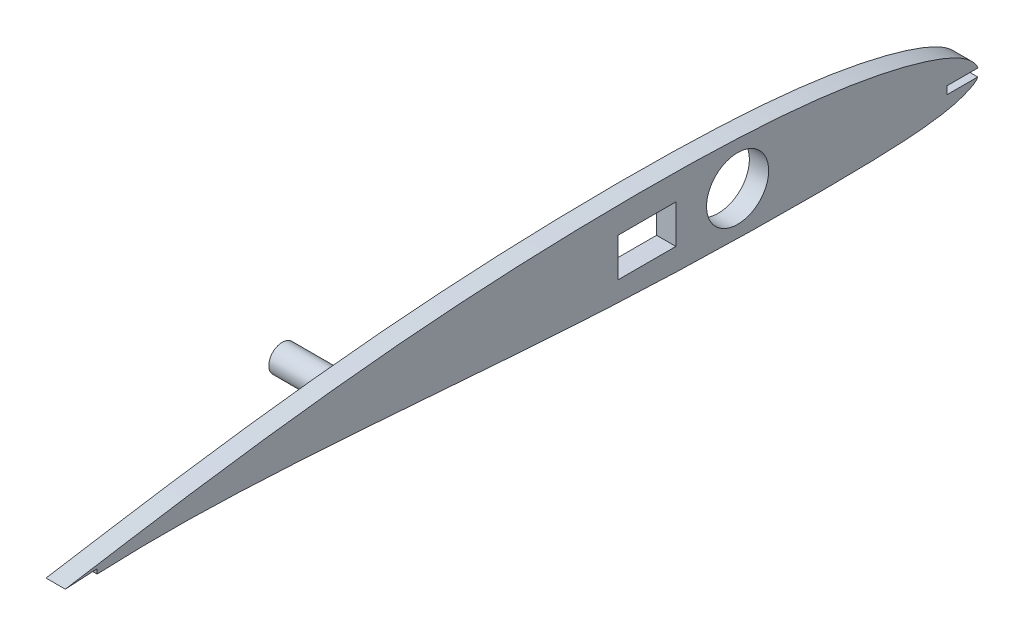
SolidWorks part; units mm, degrees
material "Manual Density from Real Component Centina"
ref_plane "Piano frontale" through (0, 0, 0) normal (0, 0, 1) x (1, 0, 0)
ref_plane "Piano superiore" through (0, 0, 0) normal (0, 1, 0) x (1, 0, 0)
ref_plane "Piano destro" through (0, 0, 0) normal (1, 0, 0) x (0, 0, -1)
curve "Curva1"
  spline degree 3 poles (0, 0.1724, 248.285) (0, -0.053, 250.4273) (0, 0.2462, 248.3284) (0, 0.5529, 246.6445) (0, 1.2459, 242.6221) (0, 2.0989, 237.7464) (0, 3.1818, 231.3634) (0, 4.2933, 223.9772) (0, 5.7312, 215.5604) (0, 7.1315, 206.3004) (0, 8.6324, 196.1631) (0, 10.1162, 185.3524) (0, 11.5493, 173.9891) (0, 12.8816, 162.1914) (0, 14.0593, 150.0724) (0, 15.0523, 137.7438) (0, 15.8256, 125.3116) (0, 16.3834, 112.8888) (0, 16.7267, 100.597) (0, 16.8648, 88.5669) (0, 16.792, 76.9314) (0, 16.4941, 65.8165) (0, 15.9609, 55.3329) (0, 15.1594, 45.573) (0, 14.0978, 36.6074) (0, 12.7884, 28.4972) (0, 11.2839, 21.2988) (0, 9.6413, 15.0749) (0, 7.9136, 9.8809) (0, 6.1182, 5.7699) (0, 4.2384, 2.7289) (0, 2.3057, 0.8126) (0, 0.7927, 0.0312) (0, -0.4105, -0.0213) (0, -1.7115, 0.4949) (0, -2.8658, 2.6253) (0, -4.0404, 5.6977) (0, -4.9287, 10.0719) (0, -5.5974, 15.6262) (0, -6.0122, 22.4122) (0, -6.265, 30.3619) (0, -6.3814, 39.3972) (0, -6.3554, 49.3987) (0, -6.2185, 60.2453) (0, -5.9476, 71.8018) (0, -5.5368, 83.9408) (0, -4.9386, 96.5461) (0, -4.1527, 109.5201) (0, -3.2196, 122.7671) (0, -2.1909, 136.1764) (0, -1.148, 149.6158) (0, -0.1602, 162.9314) (0, 0.706, 175.9537) (0, 1.3896, 188.4999) (0, 1.8332, 200.3712) (0, 1.9676, 211.3376) (0, 1.8232, 221.1842) (0, 1.4973, 229.6804) (0, 1.0741, 236.8065) (0, 0.6857, 242.1894) (0, 0.3087, 246.5181) (0, 0.1724, 248.285) (0, -0.053, 250.4273) (0, 0.2462, 248.3284) knots -0.014202 -0.006329 -0.001589 0 0.001576 0.006211 0.01368 0.023764 0.036307 0.051658 0.068045 0.086769 0.107053 0.128647 0.151303 0.174786 0.19886 0.223309 0.247929 0.272522 0.296848 0.320648 0.343669 0.365658 0.3864 0.405741 0.423561 0.439779 0.454311 0.467034 0.477831 0.486643 0.493542 0.498786 0.50271 0.50309 0.505896 0.510322 0.516831 0.525521 0.536535 0.549945 0.565696 0.583577 0.603379 0.624844 0.647727 0.671743 0.696673 0.722357 0.748609 0.77521 0.801891 0.828329 0.854175 0.879074 0.902636 0.924421 0.943939 0.960827 0.974827 0.985798 0.993671 0.998411 1 1.001576 1.006211 1.01368 periodic
sketch "Schizzo1" plane through (0, 0, 0) normal (1, 0, 0) x (0, 0, -1)
  line L0 (-250, 0) -> (0.0001, 0.0174) construction
  line L1 (0.0001, 0.0174) -> (-0.0034, 50.0174) construction
  line L2 (-62.4999, 16.3096) -> (-62.4999, -6.155) construction
  line L4 (-78.4999, 10.0773) -> (-93.4999, 10.0773)
  line L5 (-78.4999, 10.0773) -> (-78.4999, 0.0773)
  line L6 (-78.4999, 0.0773) -> (-93.4999, 0.0773)
  line L7 (-93.4999, 10.0773) -> (-93.4999, 0.0773)
  circle A0 centre (-62.4999, 5.0773) radius 8.05
  spline S0 degree 3 poles (-248.3284, 0.2462) (-250.4273, -0.053) (-248.285, 0.1724) (-246.5181, 0.3087) (-242.1894, 0.6857) (-236.8065, 1.0741) (-229.6804, 1.4973) (-221.1842, 1.8232) (-211.3376, 1.9676) (-200.3712, 1.8332) (-188.4999, 1.3896) (-175.9537, 0.706) (-162.9314, -0.1602) (-149.6158, -1.148) (-136.1764, -2.1909) (-122.7671, -3.2196) (-109.5201, -4.1527) (-96.5461, -4.9386) (-83.9408, -5.5368) (-71.8018, -5.9476) (-60.2453, -6.2185) (-49.3987, -6.3554) (-39.3972, -6.3814) (-30.3619, -6.265) (-22.4122, -6.0122) (-15.6262, -5.5974) (-10.0719, -4.9287) (-5.6977, -4.0404) (-2.6253, -2.8658) (-0.4949, -1.7115) (0.0213, -0.4105) (-0.0312, 0.7927) (-0.8126, 2.3057) (-2.7289, 4.2384) (-5.7699, 6.1182) (-9.8809, 7.9136) (-15.0749, 9.6413) (-21.2988, 11.2839) (-28.4972, 12.7884) (-36.6074, 14.0978) (-45.573, 15.1594) (-55.3329, 15.9609) (-65.8165, 16.4941) (-76.9314, 16.792) (-88.5669, 16.8648) (-100.597, 16.7267) (-112.8888, 16.3834) (-125.3116, 15.8256) (-137.7438, 15.0523) (-150.0724, 14.0593) (-162.1914, 12.8816) (-173.9891, 11.5493) (-185.3524, 10.1162) (-196.1631, 8.6324) (-206.3004, 7.1315) (-215.5604, 5.7312) (-223.9772, 4.2933) (-231.3634, 3.1818) (-237.7464, 2.0989) (-242.6221, 1.2459) (-246.6445, 0.5529) (-248.3284, 0.2462) (-250.4273, -0.053) (-248.285, 0.1724) knots -0.01368 -0.006211 -0.001576 0 0.001589 0.006329 0.014202 0.025173 0.039173 0.056061 0.075579 0.097364 0.120926 0.145825 0.171671 0.198109 0.22479 0.251391 0.277643 0.303327 0.328257 0.352273 0.375156 0.396621 0.416423 0.434304 0.450055 0.463465 0.474479 0.483169 0.489678 0.494104 0.49691 0.49729 0.501214 0.506458 0.513357 0.522169 0.532966 0.545689 0.560221 0.576439 0.594259 0.6136 0.634342 0.656331 0.679352 0.703152 0.727478 0.752071 0.776691 0.80114 0.825214 0.848697 0.871353 0.892947 0.913231 0.931955 0.948342 0.963693 0.976236 0.98632 0.993789 0.998424 1 1.001589 1.006329 1.014202 only from (-250, 0) to (-250, 0) construction
  spline S1 degree 3 poles (-248.3284, 0.2462) (-250.4273, -0.053) (-248.285, 0.1724) (-246.5181, 0.3087) (-242.1894, 0.6857) (-236.8065, 1.0741) (-229.6804, 1.4973) (-221.1842, 1.8232) (-211.3376, 1.9676) (-200.3712, 1.8332) (-188.4999, 1.3896) (-175.9537, 0.706) (-162.9314, -0.1602) (-149.6158, -1.148) (-136.1764, -2.1909) (-122.7671, -3.2196) (-109.5201, -4.1527) (-96.5461, -4.9386) (-83.9408, -5.5368) (-71.8018, -5.9476) (-60.2453, -6.2185) (-49.3987, -6.3554) (-39.3972, -6.3814) (-30.3619, -6.265) (-22.4122, -6.0122) (-15.6262, -5.5974) (-10.0719, -4.9287) (-5.6977, -4.0404) (-2.6253, -2.8658) (-0.4949, -1.7115) (0.0213, -0.4105) (-0.0312, 0.7927) (-0.8126, 2.3057) (-2.7289, 4.2384) (-5.7699, 6.1182) (-9.8809, 7.9136) (-15.0749, 9.6413) (-21.2988, 11.2839) (-28.4972, 12.7884) (-36.6074, 14.0978) (-45.573, 15.1594) (-55.3329, 15.9609) (-65.8165, 16.4941) (-76.9314, 16.792) (-88.5669, 16.8648) (-100.597, 16.7267) (-112.8888, 16.3834) (-125.3116, 15.8256) (-137.7438, 15.0523) (-150.0724, 14.0593) (-162.1914, 12.8816) (-173.9891, 11.5493) (-185.3524, 10.1162) (-196.1631, 8.6324) (-206.3004, 7.1315) (-215.5604, 5.7312) (-223.9772, 4.2933) (-231.3634, 3.1818) (-237.7464, 2.0989) (-242.6221, 1.2459) (-246.6445, 0.5529) (-248.3284, 0.2462) (-250.4273, -0.053) (-248.285, 0.1724) knots -0.01368 -0.006211 -0.001576 0 0.001589 0.006329 0.014202 0.025173 0.039173 0.056061 0.075579 0.097364 0.120926 0.145825 0.171671 0.198109 0.22479 0.251391 0.277643 0.303327 0.328257 0.352273 0.375156 0.396621 0.416423 0.434304 0.450055 0.463465 0.474479 0.483169 0.489678 0.494104 0.49691 0.49729 0.501214 0.506458 0.513357 0.522169 0.532966 0.545689 0.560221 0.576439 0.594259 0.6136 0.634342 0.656331 0.679352 0.703152 0.727478 0.752071 0.776691 0.80114 0.825214 0.848697 0.871353 0.892947 0.913231 0.931955 0.948342 0.963693 0.976236 0.98632 0.993789 0.998424 1 1.001589 1.006329 1.014202 only from (-250, 0) to (-250, 0)
  point P11 (-78.4999, 5.0773)
  dimension "D3" = 16.1
  dimension "D1" = 50
  dimension "D2" = 62.5
  dimension "D4" = 15
  dimension "D5" = 10
  dimension "D6" = 16
extrude "CorpoCentina" add sketch "Schizzo1" along normal blind 5
sketch "Schizzo2" plane through (0, 0, 0) normal (-1, 0, 0) x (0, 0, 1)
  circle A0 centre (160.4999, 6.0773) radius 3.5
  circle A1 centre (62.4999, 5.0773) radius 8.05 construction
  dimension "D1" = 7
  dimension "D2" = 98
  dimension "D3" = 1
extrude "PernoAggancio" add sketch "Schizzo2" along normal blind 15 and the other way blind 20
sketch "Schizzo3" plane through (20, 0, 0) normal (1, 0, 0) x (0, 0, -1)
  circle A0 centre (-160.4999, 6.0773) radius 3.5
  circle A1 centre (-160.4999, 6.0773) radius 3.5 construction
extrude "RimozionePernoDestro" cut sketch "Schizzo3" against normal up to surface (15 mm away) up to face at (5, 6.0773, 163.9999)
sketch "Schizzo4" plane through (5, 0, 0) normal (1, 0, 0) x (0, 0, -1)
  line L0 (0, 0) -> (-78.4999, 5.0773) construction
  line L5 (-8.1999, 1) -> (0.0001, 1)
  line L6 (-8.1999, 1) -> (-8.1999, -1)
  line L7 (-8.1999, -1) -> (0.0001, -1)
  line L8 (0.0001, 1) -> (0.0001, -1)
  line L9 (-78.4999, 0.0773) -> (-78.4999, 10.0773) construction
  spline S1 degree 3 poles (-248.3284, 0.2462) (-250.4273, -0.053) (-248.285, 0.1724) (-246.5181, 0.3087) (-242.1894, 0.6857) (-236.8065, 1.0741) (-229.6804, 1.4973) (-221.1842, 1.8232) (-211.3376, 1.9676) (-200.3712, 1.8332) (-188.4999, 1.3896) (-175.9537, 0.706) (-162.9314, -0.1602) (-149.6158, -1.148) (-136.1764, -2.1909) (-122.7671, -3.2196) (-109.5201, -4.1527) (-96.5461, -4.9386) (-83.9408, -5.5368) (-71.8018, -5.9476) (-60.2453, -6.2185) (-49.3987, -6.3554) (-39.3972, -6.3814) (-30.3619, -6.265) (-22.4122, -6.0122) (-15.6262, -5.5974) (-10.0719, -4.9287) (-5.6977, -4.0404) (-2.6253, -2.8658) (-0.4949, -1.7115) (0.0213, -0.4105) (-0.0312, 0.7927) (-0.8126, 2.3057) (-2.7289, 4.2384) (-5.7699, 6.1182) (-9.8809, 7.9136) (-15.0749, 9.6413) (-21.2988, 11.2839) (-28.4972, 12.7884) (-36.6074, 14.0978) (-45.573, 15.1594) (-55.3329, 15.9609) (-65.8165, 16.4941) (-76.9314, 16.792) (-88.5669, 16.8648) (-100.597, 16.7267) (-112.8888, 16.3834) (-125.3116, 15.8256) (-137.7438, 15.0523) (-150.0724, 14.0593) (-162.1914, 12.8816) (-173.9891, 11.5493) (-185.3524, 10.1162) (-196.1631, 8.6324) (-206.3004, 7.1315) (-215.5604, 5.7312) (-223.9772, 4.2933) (-231.3634, 3.1818) (-237.7464, 2.0989) (-242.6221, 1.2459) (-246.6445, 0.5529) (-248.3284, 0.2462) (-250.4273, -0.053) (-248.285, 0.1724) knots -0.01368 -0.006211 -0.001576 0 0.001589 0.006329 0.014202 0.025173 0.039173 0.056061 0.075579 0.097364 0.120926 0.145825 0.171671 0.198109 0.22479 0.251391 0.277643 0.303327 0.328257 0.352273 0.375156 0.396621 0.416423 0.434304 0.450055 0.463465 0.474479 0.483169 0.489678 0.494104 0.49691 0.49729 0.501214 0.506458 0.513357 0.522169 0.532966 0.545689 0.560221 0.576439 0.594259 0.6136 0.634342 0.656331 0.679352 0.703152 0.727478 0.752071 0.776691 0.80114 0.825214 0.848697 0.871353 0.892947 0.913231 0.931955 0.948342 0.963693 0.976236 0.98632 0.993789 0.998424 1 1.001589 1.006329 1.014202 only from (-250, 0) to (-250, 0) construction
  point P10 (0.0001, 0)
  dimension "D1" = 2
  dimension "D2" = 8.2
extrude "IntaglioAnteriore" cut sketch "Schizzo4" against normal through all
sketch "Schizzo5" plane through (0, 0, 0) normal (-1, 0, 0) x (0, 0, 1)
  line L0 (228.544, 2.7244) -> (228.4772, 1.5262)
  line L1 (228.4772, 1.5262) -> (236.6645, 1.07)
  line L2 (236.6645, 1.07) -> (236.7313, 2.2681)
  line L3 (236.7313, 2.2681) -> (228.544, 2.7244)
  spline S1 degree 3 poles (0.2015, 1) (0.3423, 1.3625) (1.0086, 2.5034) (2.7289, 4.2384) (5.7699, 6.1182) (9.8809, 7.9136) (15.0749, 9.6413) (21.2988, 11.2839) (28.4972, 12.7884) (36.6074, 14.0978) (45.573, 15.1594) (55.3329, 15.9609) (65.8165, 16.4941) (76.9314, 16.792) (88.5669, 16.8648) (100.597, 16.7267) (112.8888, 16.3834) (125.3116, 15.8256) (137.7438, 15.0523) (150.0724, 14.0593) (162.1914, 12.8816) (173.9891, 11.5493) (185.3524, 10.1162) (196.1631, 8.6324) (206.3004, 7.1315) (215.5604, 5.7312) (223.9772, 4.2933) (231.3634, 3.1818) (237.7464, 2.0989) (242.6221, 1.2459) (246.6445, 0.5529) (248.3284, 0.2462) (250.4273, -0.053) (248.285, 0.1724) (246.5181, 0.3087) (242.1894, 0.6857) (236.8065, 1.0741) (229.6804, 1.4973) (221.1842, 1.8232) (211.3376, 1.9676) (200.3712, 1.8332) (188.4999, 1.3896) (175.9537, 0.706) (162.9314, -0.1602) (149.6158, -1.148) (136.1764, -2.1909) (122.7671, -3.2196) (109.5201, -4.1527) (96.5461, -4.9386) (83.9408, -5.5368) (71.8018, -5.9476) (60.2453, -6.2185) (49.3987, -6.3554) (39.3972, -6.3814) (30.3619, -6.265) (22.4122, -6.0122) (15.6262, -5.5974) (10.0719, -4.9287) (5.6977, -4.0404) (2.6253, -2.8658) (0.8093, -1.8819) (0.3291, -1.1192) (0.2665, -1) knots 0.498933 0.498933 0.498933 0.498933 0.501214 0.506458 0.513357 0.522169 0.532966 0.545689 0.560221 0.576439 0.594259 0.6136 0.634342 0.656331 0.679352 0.703152 0.727478 0.752071 0.776691 0.80114 0.825214 0.848697 0.871353 0.892947 0.913231 0.931955 0.948342 0.963693 0.976236 0.98632 0.993789 0.998424 1 1.001589 1.006329 1.014202 1.025173 1.039173 1.056061 1.075579 1.097364 1.120926 1.145825 1.171671 1.198109 1.22479 1.251391 1.277643 1.303327 1.328257 1.352273 1.375156 1.396621 1.416423 1.434304 1.450055 1.463465 1.474479 1.483169 1.489678 1.494104 1.494882 1.494882 1.494882 1.494882 construction
  dimension "D1" = 8.2
  dimension "D2" = 1.2
extrude "IntaglioPosteriore1" cut sketch "Schizzo5" against normal through all
sketch "Schizzo6" plane through (0, 0, 0) normal (-1, 0, 0) x (0, 0, 1)
  line L0 (236.9028, 5.3465) -> (236.4691, -2.4383)
  line L1 (236.4691, -2.4383) -> (253.4453, -3.3842)
  line L3 (253.4453, -3.3842) -> (253.8791, 4.4005)
  line L4 (253.8791, 4.4005) -> (236.9028, 5.3465)
  line L5 (236.6645, 1.07) -> (236.7313, 2.2681) construction
  dimension "D1" = 7.7847
  dimension "D2" = 16.9762
  dimension "D3" = 3.9645
extrude "IntaglioPosteriore2" cut sketch "Schizzo6" against normal through all
